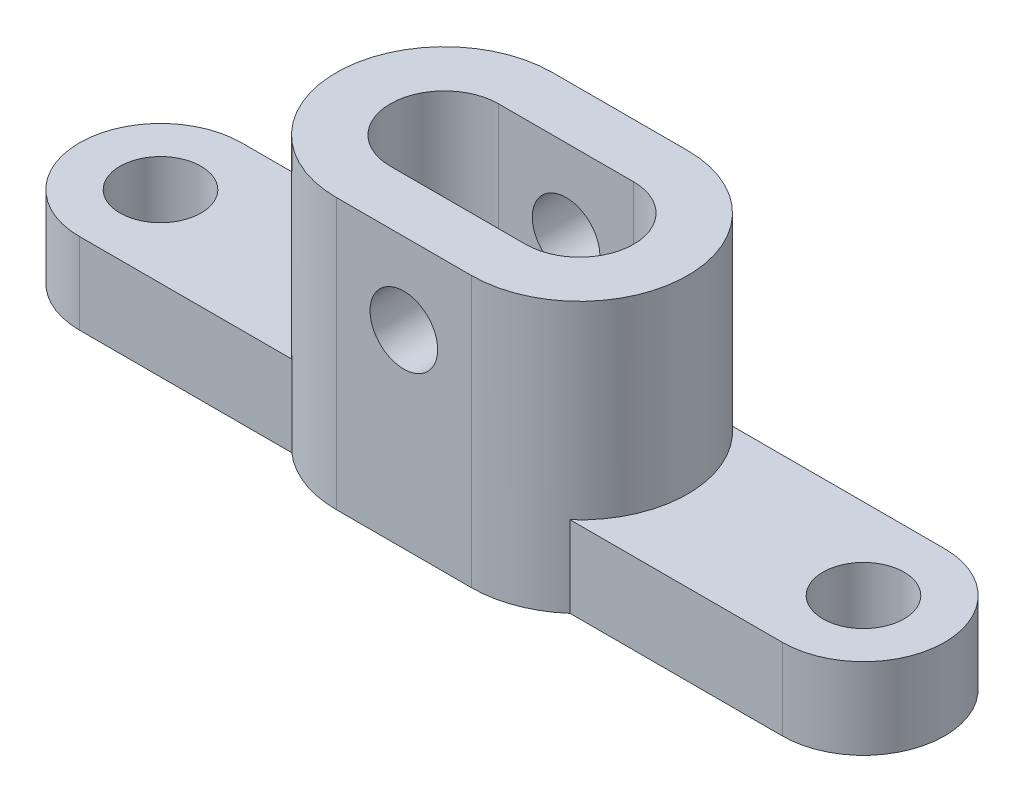
SolidWorks part; units mm, degrees
ref_plane "前视基准面" through (0, 0, 0) normal (0, 0, 1) x (1, 0, 0)
ref_plane "上视基准面" through (0, 0, 0) normal (0, 1, 0) x (1, 0, 0)
ref_plane "右视基准面" through (0, 0, 0) normal (1, 0, 0) x (0, 0, -1)
sketch "草图1" plane through (0, 0, 0) normal (0, 1, 0) x (1, 0, 0)
  line L0 (0, 0) -> (26, 0) construction
  line L11 (0, 3) -> (26, 3)
  line L12 (0, -3) -> (26, -3)
  arc A0 (0, 3) -> (0, -3) centre (0, 0) ccw
  arc A1 (26, -3) -> (26, 3) centre (26, 0) ccw
  circle A2 centre (0, 0) radius 1.5
  circle A3 centre (26, 0) radius 1.5
  point P2 (13, 0)
  dimension "D3" = 3
  dimension "D4" = 3
  dimension "D1" = 26
  dimension "D2" = 6
extrude "凸台-拉伸1" add sketch "草图1" along normal blind 3
sketch "草图6" plane through (0, 0, 0) normal (0, -1, 0) x (1, 0, 0)
  line L0 (10.5, 0) -> (15.5, 0) construction
  line L1 (10.5, 4) -> (15.5, 4)
  line L2 (10.5, -4) -> (15.5, -4)
  arc A0 (10.5, 4) -> (10.5, -4) centre (10.5, 0) ccw
  arc A1 (15.5, -4) -> (15.5, 4) centre (15.5, 0) ccw
  circle A2 centre (26, 0) radius 1.5 construction
  point P2 (13, 0)
  dimension "D1" = 13
  dimension "D2" = 8
  dimension "D3" = 5
extrude "凸台-拉伸2" add sketch "草图6" against normal blind 10
sketch "草图7" plane through (0, 0, -4) normal (0, 0, -1) x (-1, 0, 0)
  line L0 (-10.5, 10) -> (-15.5, 10) construction
  circle A0 centre (-13, 7) radius 1.25
  dimension "D1" = 2.5
  dimension "D2" = 3
extrude "切除-拉伸7" cut sketch "草图7" against normal through all
sketch "草图9" plane through (0, 10, 0) normal (0, 1, 0) x (1, 0, 0)
  line L6 (10.5, -2) -> (15.5, -2)
  line L7 (15.5, 2) -> (10.5, 2)
  line L8 (10.5, -2) -> (15.5, -2)
  line L9 (15.5, 2) -> (10.5, 2)
  arc A8 (10.5, 2) -> (10.5, -2) centre (10.5, 0) ccw
  arc A9 (15.5, -2) -> (15.5, 2) centre (15.5, 0) ccw
  arc A10 (10.5, 2) -> (10.5, -2) centre (10.5, 0) ccw
  arc A11 (15.5, -2) -> (15.5, 2) centre (15.5, 0) ccw
  dimension "D1" = 2
extrude "切除-拉伸8" cut sketch "草图9" against normal through all
